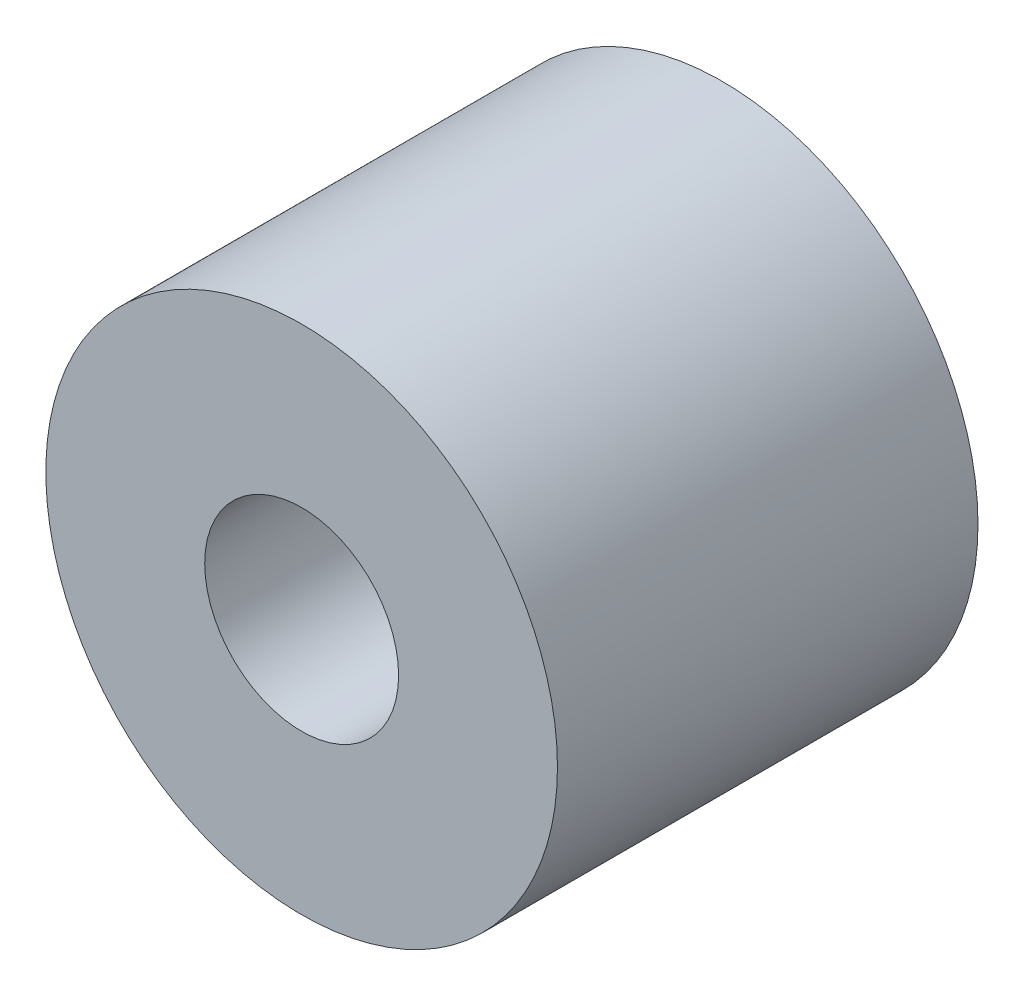
SolidWorks part; units mm, degrees
ref_plane "Front Plane" through (0, 0, 0) normal (0, 0, 1) x (1, 0, 0)
ref_plane "Top Plane" through (0, 0, 0) normal (0, 1, 0) x (1, 0, 0)
ref_plane "Right Plane" through (0, 0, 0) normal (1, 0, 0) x (0, 0, -1)
sketch "Sketch1" plane through (0, 0, 0) normal (0, 0, 1) x (1, 0, 0)
  circle A0 centre (0, 0) radius 10.95
  circle A1 centre (0, 0) radius 4.15
  dimension "D1" = 21.9
  dimension "D2" = 8.3
extrude "Boss-Extrude1" add sketch "Sketch1" along normal blind 18
